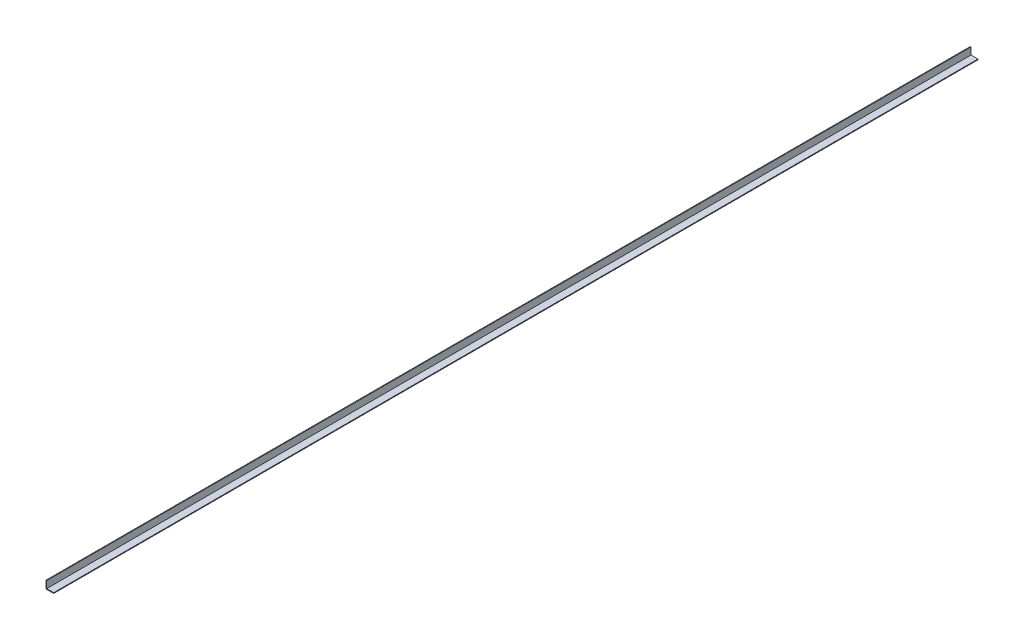
SolidWorks part; units mm, degrees
material "ASTM A36 Acero"
ref_plane "Alzado" through (0, 0, 0) normal (0, 0, 1) x (1, 0, 0)
ref_plane "Planta" through (0, 0, 0) normal (0, 1, 0) x (1, 0, 0)
ref_plane "Vista lateral" through (0, 0, 0) normal (1, 0, 0) x (0, 0, -1)
sketch "Croquis1" plane through (0, 0, 0) normal (0, 0, 1) x (1, 0, 0)
  line L0 (0, 50.8) -> (0, 0)
  line L1 (0, 0) -> (50.8, 0)
  line L2 (50.8, 0) -> (50.8, 4.76)
  line L3 (50.8, 4.76) -> (4.76, 4.76)
  line L4 (4.76, 4.76) -> (4.76, 50.8)
  line L5 (4.76, 50.8) -> (0, 50.8)
  dimension "D1" = 4.76
  dimension "D2" = 50.8
extrude "Saliente-Extruir1" add sketch "Croquis1" against normal blind 6100
